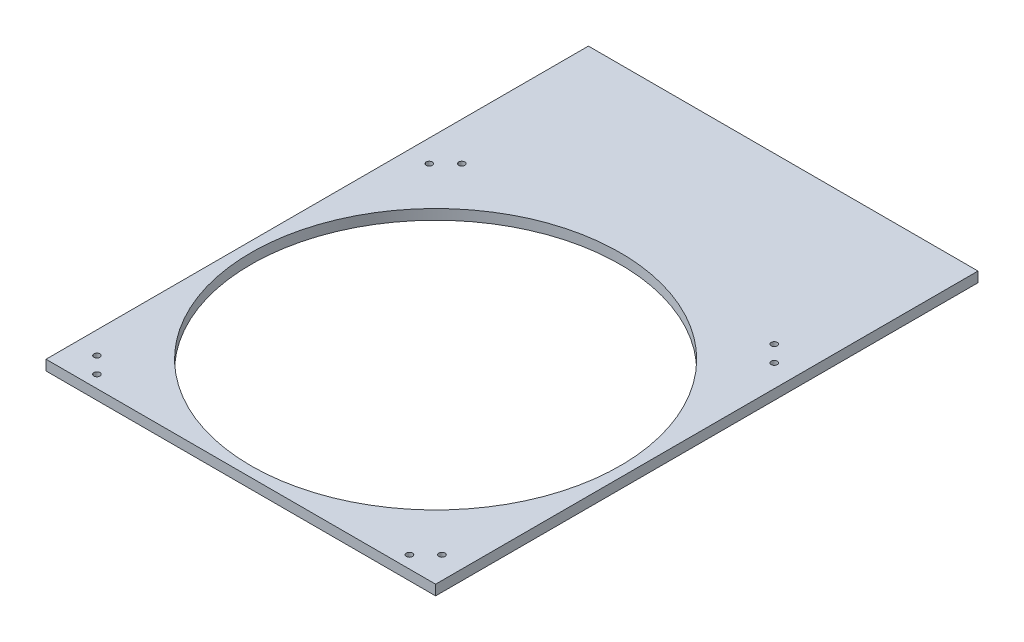
SolidWorks part; units mm, degrees
ref_plane "Front Plane" through (0, 0, 0) normal (0, 0, 1) x (1, 0, 0)
ref_plane "Top Plane" through (0, 0, 0) normal (0, 1, 0) x (1, 0, 0)
ref_plane "Right Plane" through (0, 0, 0) normal (1, 0, 0) x (0, 0, -1)
sketch "Sketch1" plane through (0, 0, 0) normal (0, 1, 0) x (1, 0, 0)
  line L0 (114.497, 374.8331) -> (357.3845, 374.8331)
  line L5 (114.497, 374.8331) -> (114.497, 36.6956)
  line L6 (114.497, 36.6956) -> (357.3845, 36.6956)
  line L7 (357.3845, 374.8331) -> (357.3845, 36.6956)
  circle A0 centre (235.9407, 158.1394) radius 115.0937
extrude "Boss-Extrude1" add sketch "Sketch1" along normal blind 6.35
sketch "Sketch7" plane through (0, 0, 0) normal (0, -1, 0) x (1, 0, 0)
  line L2 (235.9407, -43.0456) -> (235.9407, -158.1394) construction
  line L4 (235.9407, -158.1394) -> (351.0345, -158.1394) construction
  circle A2 centre (138.5265, -44.4161) radius 1.905
  circle A3 centre (128.389, -54.5536) radius 1.905
  circle A4 centre (235.9407, -158.1394) radius 115.0937 construction
  circle A5 centre (343.4924, -54.5536) radius 1.905
  circle A6 centre (333.3549, -44.4161) radius 1.905
  circle A7 centre (333.3549, -271.8627) radius 1.905
  circle A8 centre (343.4924, -261.7252) radius 1.905
  circle A9 centre (128.389, -261.7252) radius 1.905
  circle A10 centre (138.5265, -271.8627) radius 1.905
extrude "Cut-Extrude1" cut sketch "Sketch7" against normal through all
